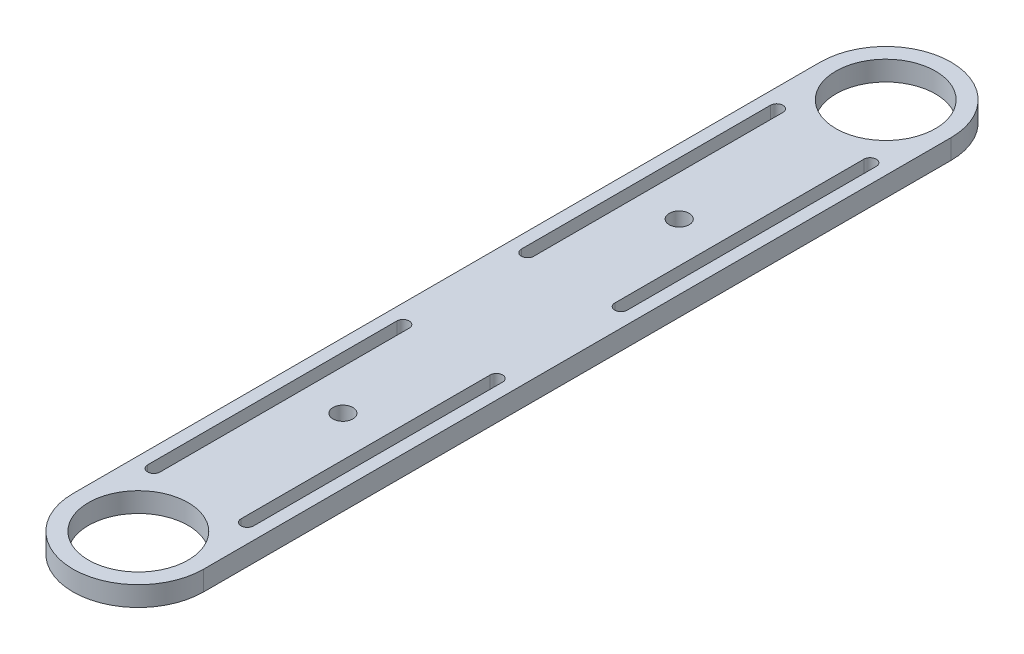
SolidWorks part; units mm, degrees
ref_plane "Front Plane" through (0, 0, 0) normal (0, 0, 1) x (1, 0, 0)
ref_plane "Top Plane" through (0, 0, 0) normal (0, 1, 0) x (1, 0, 0)
ref_plane "Right Plane" through (0, 0, 0) normal (1, 0, 0) x (0, 0, -1)
sketch "Sketch1" plane through (0, 0, 0) normal (0, 1, 0) x (1, 0, 0)
  line L0 (-10.5, 0) -> (-10.5, -120)
  line L1 (10.5, 0) -> (10.5, -120)
  arc A0 (10.5, 0) -> (-10.5, 0) centre (0, 0) ccw
  arc A1 (-10.5, -120) -> (10.5, -120) centre (0, -120) ccw
  dimension "D1" = 10.5
  dimension "D2" = 120
extrude "Boss-Extrude1" add sketch "Sketch1" along normal blind 3.175
sketch "Sketch3" plane through (0, 0, 0) normal (0, -1, 0) x (1, 0, 0)
  line L0 (-8.5, 110) -> (-8.5, 70) construction
  line L1 (-6.5, 70) -> (-6.5, 110) construction
  line L2 (6.5, 110) -> (6.5, 70) construction
  line L3 (8.5, 70) -> (8.5, 110) construction
  line L4 (8.5, 10) -> (8.5, 50) construction
  line L5 (6.5, 50) -> (6.5, 10) construction
  line L6 (-8.5, 50) -> (-8.5, 10) construction
  line L7 (-6.5, 10) -> (-6.5, 50) construction
  line L8 (-8.5, 110) -> (-8.5, 70)
  line L9 (-6.5, 70) -> (-6.5, 110)
  line L10 (6.5, 110) -> (6.5, 70)
  line L11 (8.5, 70) -> (8.5, 110)
  line L12 (8.5, 10) -> (8.5, 50)
  line L13 (6.5, 50) -> (6.5, 10)
  line L14 (-8.5, 50) -> (-8.5, 10)
  line L15 (-6.5, 10) -> (-6.5, 50)
  arc A1 (-8.5, 70) -> (-6.5, 70) centre (-7.5, 70) ccw construction
  arc A2 (8.5, 110) -> (6.5, 110) centre (7.5, 110) ccw construction
  arc A3 (6.5, 70) -> (8.5, 70) centre (7.5, 70) ccw construction
  arc A4 (6.5, 10) -> (8.5, 10) centre (7.5, 10) ccw construction
  arc A5 (8.5, 50) -> (6.5, 50) centre (7.5, 50) ccw construction
  arc A6 (-6.5, 50) -> (-8.5, 50) centre (-7.5, 50) ccw construction
  arc A7 (-8.5, 10) -> (-6.5, 10) centre (-7.5, 10) ccw construction
  arc A8 (-8.5, 70) -> (-6.5, 70) centre (-7.5, 70) ccw
  arc A9 (8.5, 110) -> (6.5, 110) centre (7.5, 110) ccw
  arc A10 (6.5, 70) -> (8.5, 70) centre (7.5, 70) ccw
  arc A11 (6.5, 10) -> (8.5, 10) centre (7.5, 10) ccw
  arc A12 (8.5, 50) -> (6.5, 50) centre (7.5, 50) ccw
  arc A13 (-6.5, 50) -> (-8.5, 50) centre (-7.5, 50) ccw
  arc A14 (-8.5, 10) -> (-6.5, 10) centre (-7.5, 10) ccw
  arc A15 (-6.5, 110) -> (-8.5, 110) centre (-7.5, 110) ccw construction
  arc A16 (-6.5, 110) -> (-8.5, 110) centre (-7.5, 110) ccw
extrude "Cut-Extrude2" cut sketch "Sketch3" against normal through all both and the other way through all
sketch "Sketch4" plane through (0, 3.175, 0) normal (0, 1, 0) x (1, 0, 0)
  circle A0 centre (0, -33.15) radius 1.6 construction
  circle A1 centre (0, -87.15) radius 1.6 construction
  circle A2 centre (0, -33.15) radius 1.6
  circle A3 centre (0, -87.15) radius 1.6
extrude "Cut-Extrude3" cut sketch "Sketch4" against normal through all both and the other way through all
sketch "Sketch5" plane through (0, 3.175, 0) normal (0, 1, 0) x (1, 0, 0)
  circle A0 centre (0, 0) radius 8 construction
  circle A1 centre (0, -120) radius 8 construction
  circle A2 centre (0, 0) radius 8
  circle A3 centre (0, -120) radius 8
extrude "Cut-Extrude4" cut sketch "Sketch5" against normal through all both and the other way through all
